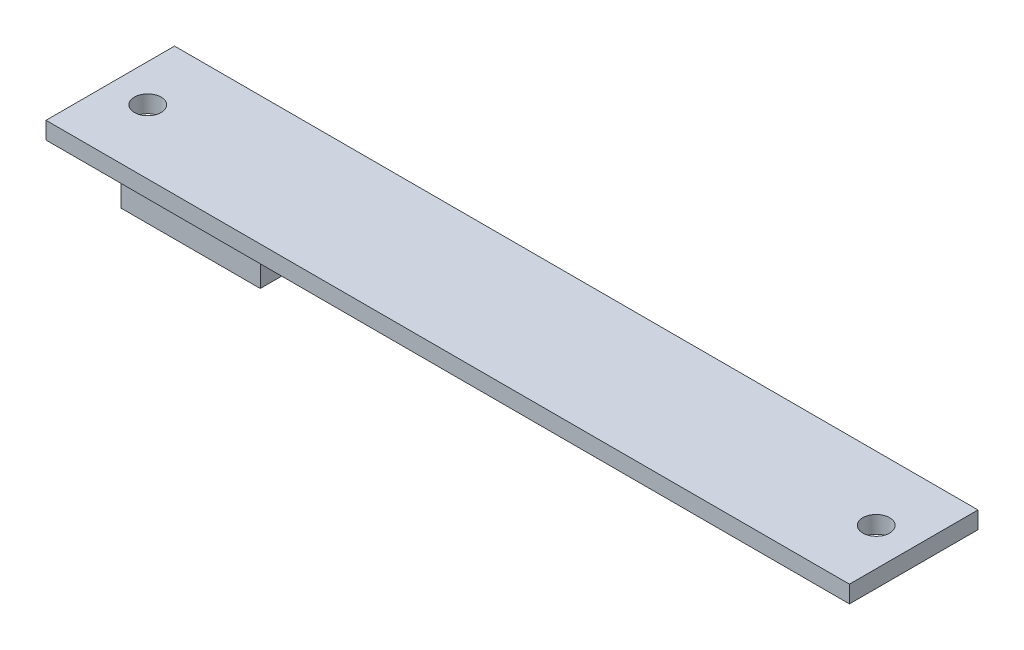
SolidWorks part; units mm, degrees
ref_plane "Front Plane" through (0, 0, 0) normal (0, 0, 1) x (1, 0, 0)
ref_plane "Top Plane" through (0, 0, 0) normal (0, 1, 0) x (1, 0, 0)
ref_plane "Right Plane" through (0, 0, 0) normal (1, 0, 0) x (0, 0, -1)
sketch "Sketch1" plane through (0, 0, 0) normal (0, 1, 0) x (1, 0, 0)
  line L1 (0, 0) -> (-75, 0)
  line L2 (0, 0) -> (0, 12)
  line L3 (0, 12) -> (-75, 12)
  line L4 (-75, 0) -> (-75, 12)
  dimension "D1" = 12
  dimension "D2" = 75
extrude "pcb" add sketch "Sketch1" along normal blind 1.6
sketch "Sketch2" plane through (0, 1.6, 0) normal (0, 1, 0) x (1, 0, 0)
  line L0 (-75, 12) -> (-75, 0) construction
  line L1 (0, 0) -> (0, 12) construction
  circle A0 centre (-71.5, 6) radius 1.25
  circle A1 centre (-3.5, 6) radius 1.25
  dimension "D3" = 2.5
  dimension "D4" = 2.5
  dimension "D1" = 3.5
  dimension "D2" = 3.5
extrude "screw holes" cut sketch "Sketch2" against normal through all
sketch "Sketch3" plane through (0, 0, 0) normal (0, -1, 0) x (1, 0, 0)
  line L1 (-69, -1) -> (-56, -1)
  line L2 (-69, -1) -> (-69, -3.3)
  line L3 (-69, -3.3) -> (-56, -3.3)
  line L4 (-56, -1) -> (-56, -3.3)
  line L5 (-75, 0) -> (0, 0) construction
  line L6 (-75, -12) -> (-75, 0) construction
  point P6 (0, 0)
  dimension "D1" = 13
  dimension "D2" = 2.3
  dimension "D3" = 1
  dimension "D4" = 6
extrude "Boss-Extrude1" add sketch "Sketch3" along normal blind 3
